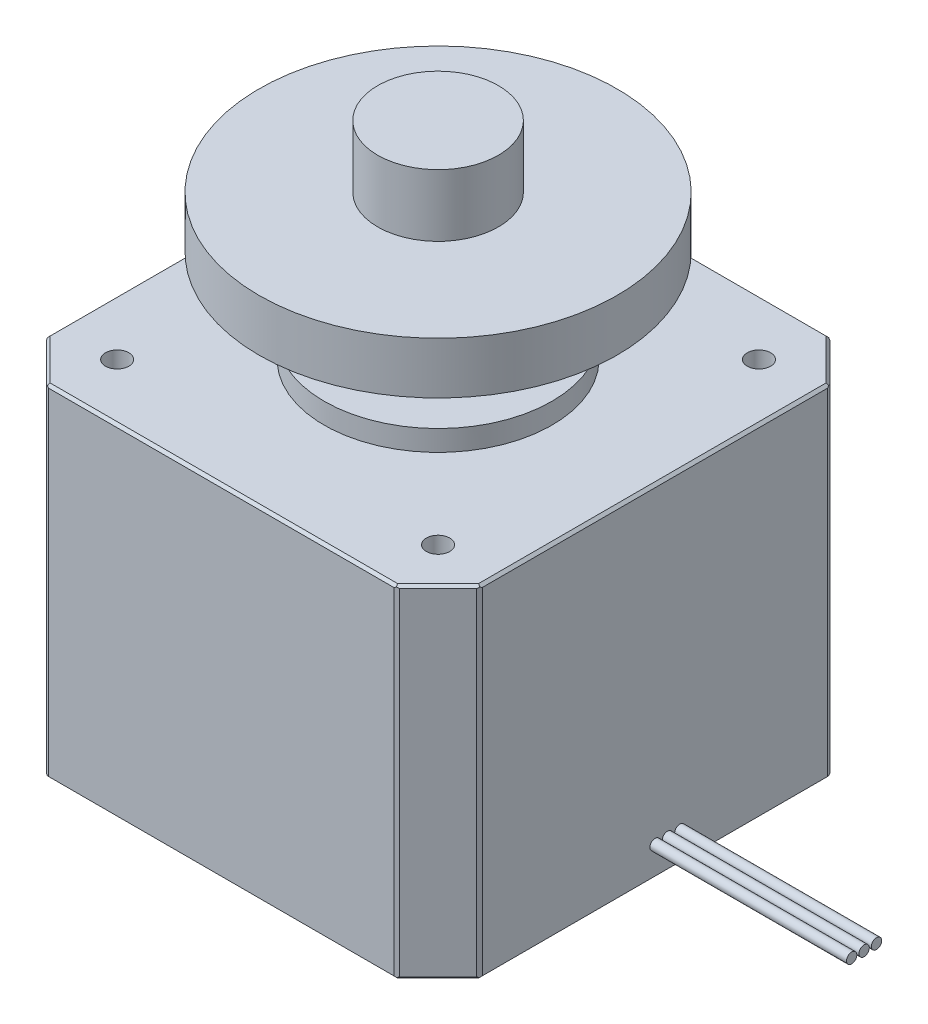
SolidWorks part; units mm, degrees
ref_plane "Front Plane" through (0, 0, 0) normal (0, 0, 1) x (1, 0, 0)
ref_plane "Top Plane" through (0, 0, 0) normal (0, 1, 0) x (1, 0, 0)
ref_plane "Right Plane" through (0, 0, 0) normal (1, 0, 0) x (0, 0, -1)
sketch "Sketch1" plane through (0, 0, 0) normal (0, 1, 0) x (1, 0, 0)
  line L1 (-20.955, -20.955) -> (20.955, -20.955)
  line L2 (-20.955, -20.955) -> (-20.955, 20.955)
  line L3 (-20.955, 20.955) -> (20.955, 20.955)
  line L4 (20.955, -20.955) -> (20.955, 20.955)
  line L5 (-20.955, -20.955) -> (20.955, 20.955) construction
  line L6 (-20.955, 20.955) -> (20.955, -20.955) construction
  point P0 (0, 0)
  dimension "D1" = 41.91
extrude "Extrude1" add sketch "Sketch1" against normal blind 33
sketch "Sketch9" plane through (0, 0, 0) normal (0, 1, 0) x (1, 0, 0)
  circle A0 centre (0, 0) radius 11
  dimension "D1" = 22
extrude "Extrude5" add sketch "Sketch9" along normal blind 2
sketch "Sketch7" plane through (0, 2, 0) normal (0, 1, 0) x (-1, 0, 0)
  circle A0 centre (0, 0) radius 2.5006
  circle A1 centre (0, 0) radius 11 construction
  dimension "D1" = 5.0013
extrude "Extrude3" add sketch "Sketch7" along normal blind 18
hole_wizard "#4-40 Tapped Hole1" positions "Sketch20" profile "Sketch19" tap size "#4-40" standard "Ansi Inch"
sketch "Sketch20" plane through (0, 0, 0) normal (0, 1, 0) x (-1, 0, 0)
  line L1 (-15.5, 15.5) -> (15.5, 15.5) construction
  line L2 (-15.5, 15.5) -> (-15.5, -15.5) construction
  line L3 (-15.5, -15.5) -> (15.5, -15.5) construction
  line L4 (15.5, 15.5) -> (15.5, -15.5) construction
  line L5 (-15.5, 15.5) -> (15.5, -15.5) construction
  line L6 (-15.5, -15.5) -> (15.5, 15.5) construction
  point P0 (15.5, -15.5)
  point P152 (15.5, 15.5)
  point P154 (-15.5, 15.5)
  point P156 (-15.5, -15.5)
  dimension "D1" = 31
  dimension "D2" = 31
sketch "Sketch19" plane through (-15.5, 0, -15.5) normal (1, 0, 0) x (0, 0, 1)
  line L0 (0, 0) -> (0, 7.0892)
  line L1 (0, 7.0892) -> (1.1303, 6.41)
  line L2 (1.1303, 6.41) -> (1.1303, 0)
  line L5 (1.1303, 0) -> (0, 0)
  line L10 (0, 7.0892) -> (-1.1303, 6.41) construction
  line L11 (0, -6.35) -> (0, 107.95) construction
  dimension "Tap Drill Dia." = 2.2606
  dimension "Tap Drill Depth" = 6.41
  dimension "Drill Angle" = 118
cosmetic thread "Hole Thread1" parameters "D1"=4.5, "D2"=2.8448
cosmetic thread "Hole Thread2" parameters "D1"=4.5, "D2"=2.8448
cosmetic thread "Hole Thread3" parameters "D1"=4.5, "D2"=2.8448
cosmetic thread "Hole Thread4" parameters "D1"=4.5, "D2"=2.8448
hole_wizard "#4-40 Tapped Hole2" positions "Sketch22" profile "Sketch21" tap size "#4-40" standard "Ansi Inch"
sketch "Sketch22" plane through (0, -33, 0) normal (0, -1, 0) x (1, 0, 0)
  point P0 (15.5, -15.5)
  point P1 (-15.5, 15.5)
  point P4 (-15.5, -15.5)
  point P7 (15.5, 15.5)
sketch "Sketch21" plane through (15.5, -33, -15.5) normal (1, 0, 0) x (0, 0, -1)
  line L0 (0, 0) -> (0, 30.5842)
  line L1 (0, 30.5842) -> (1.1303, 29.905)
  line L2 (1.1303, 29.905) -> (1.1303, 0)
  line L5 (1.1303, 0) -> (0, 0)
  line L10 (0, 30.5842) -> (-1.1303, 29.905) construction
  line L11 (0, -6.35) -> (0, 107.95) construction
  dimension "Tap Drill Dia." = 2.2606
  dimension "Tap Drill Depth" = 29.905
  dimension "Drill Angle" = 118
cosmetic thread "Hole Thread5" parameters "D1"=28, "D2"=2.8448
cosmetic thread "Hole Thread8" parameters "D1"=28, "D2"=2.8448
cosmetic thread "Hole Thread9" parameters "D1"=28, "D2"=2.8448
sketch "Sketch14" plane through (0, -33, 0) normal (0, 1, 0) x (1, 0, 0)
  line L1 (15.5, 15.5) -> (-15.5, 15.5) construction
  line L2 (15.5, 15.5) -> (15.5, -15.5) construction
  line L3 (15.5, -15.5) -> (-15.5, -15.5) construction
  line L4 (-15.5, 15.5) -> (-15.5, -15.5) construction
  line L5 (15.5, 15.5) -> (-15.5, -15.5) construction
  line L6 (15.5, -15.5) -> (-15.5, 15.5) construction
  circle A0 centre (15.5, 15.5) radius 3.1
  circle A1 centre (-15.5, 15.5) radius 3.1
  circle A2 centre (-15.5, -15.5) radius 3.1
  circle A3 centre (15.5, -15.5) radius 3.1
  point P0 (0, 0)
  dimension "D2" = 6.2
  dimension "D1" = 31
extrude "Cut-Extrude1" cut sketch "Sketch14" along normal blind 2.6
sketch "Sketch15" plane through (0, 20, 0) normal (0, 1, 0) x (1, 0, 0)
  circle A1 centre (0, 0) radius 2.5006
  circle A2 centre (0, 0) radius 2.5006
  dimension "D1" = 0
extrude "Cut-Extrude2" [suppressed] cut sketch "Sketch15" against normal blind 12.7762
chamfer "Chamfer1" distance 0.508 angle 45 1 edges at (0, 20, 2.5006)
chamfer "Chamfer2" distance 4.064 angle 45 4 edges at (-20.955, -16.5, 20.955) (20.955, -16.5, 20.955) (20.955, -16.5, -20.955) (-20.955, -16.5, -20.955)
sketch "Sketch16" plane through (0, -33, 0) normal (0, -1, 0) x (1, 0, 0)
  circle A1 centre (0, 0) radius 3.3147
  dimension "D1" = 6.6294
extrude "Cut-Extrude3" cut sketch "Sketch16" against normal blind 5.08
sketch "Sketch17" plane through (0, -27.92, 0) normal (0, -1, 0) x (1, 0, 0)
  circle A0 centre (0, 0) radius 2.5006
  circle A1 centre (0, 0) radius 2.5006 construction
  dimension "D1" = 5.0013
extrude "Boss-Extrude1" add sketch "Sketch17" along normal offset from surface (4.08 mm away) 1 up to face at (0, -33, -3.3147)
chamfer "Chamfer3" distance 0.254 angle 45 18 edges at (0, -33, -3.3147) (-20.955, -33, 0) (0, -33, -20.955) (18.923, -33, -18.923) (20.955, -33, 0) (18.923, -33, 18.923) (0, -33, 20.955) (-18.923, -33, 18.923) (0, 0, -20.955) (18.923, 0, -18.923) (20.955, 0, 0) (18.923, 0, 18.923) (0, 0, 20.955) (-18.923, 0, 18.923) (-20.955, 0, 0) (-18.923, 0, -18.923) (-18.923, -33, -18.923) (0, -32, -2.5006)
chamfer "Chamfer4" distance 0.254 angle 20 8 edges at (20.955, -16.5, -16.891) (16.891, -16.5, -20.955) (-16.891, -16.5, -20.955) (-20.955, -16.5, -16.891) (-20.955, -16.5, 16.891) (-16.891, -16.5, 20.955) (20.955, -16.5, 16.891) (16.891, -16.5, 20.955)
sketch "Sketch18" plane through (0, 20, 0) normal (0, 1, 0) x (1, 0, 0)
  line L1 (-2.5006, 3.0006) -> (2.5006, 3.0006)
  line L2 (-2.5006, 3.0006) -> (-2.5006, 2.0006)
  line L3 (-2.5006, 2.0006) -> (2.5006, 2.0006)
  line L4 (2.5006, 3.0006) -> (2.5006, 2.0006)
  line L5 (-2.5006, 3.0006) -> (2.5006, 2.0006) construction
  line L6 (-2.5006, 2.0006) -> (2.5006, 3.0006) construction
  circle A0 centre (0, 0) radius 2.5006 construction
  circle A1 centre (0, 0) radius 2.5006 construction
  point P0 (0, 2.5006)
  dimension "D1" = 0.5
extrude "Cut-Extrude4" cut sketch "Sketch18" against normal blind 15
sketch "Sketch24" plane through (20.955, 0, 0) normal (1, 0, 0) x (0, 0, -1)
  circle A0 centre (2.4, -30.0865) radius 0.5
  circle A1 centre (1.2, -30.0865) radius 0.5
  circle A2 centre (0, -30.0865) radius 0.5
  dimension "D1" = 1
  dimension "D2" = 1.2
  dimension "D3" = 1.2
extrude "Boss-Extrude2" add sketch "Sketch24" along normal blind 19
sketch "Sketch25" plane through (0, 20, 0) normal (0, 1, 0) x (1, 0, 0)
  circle A0 centre (0, 0) radius 5.83
  dimension "D1" = 11.66
extrude "Boss-Extrude3" add sketch "Sketch25" against normal blind 14
sketch "Sketch26" plane through (0, 20, 0) normal (0, 1, 0) x (1, 0, 0)
  circle A0 centre (0, 0) radius 17.29
  dimension "D1" = 34.58
extrude "Boss-Extrude4" add sketch "Sketch26" against normal blind 11
sketch "Sketch27" plane through (0, 20, 0) normal (0, 1, 0) x (1, 0, 0)
  circle A0 centre (0, 0) radius 17.29
  circle A1 centre (0, 0) radius 5.83
  circle A2 centre (0, 0) radius 17.29 construction
  circle A3 centre (0, 0) radius 5.83 construction
extrude "Cut-Extrude5" cut sketch "Sketch27" against normal blind 6
